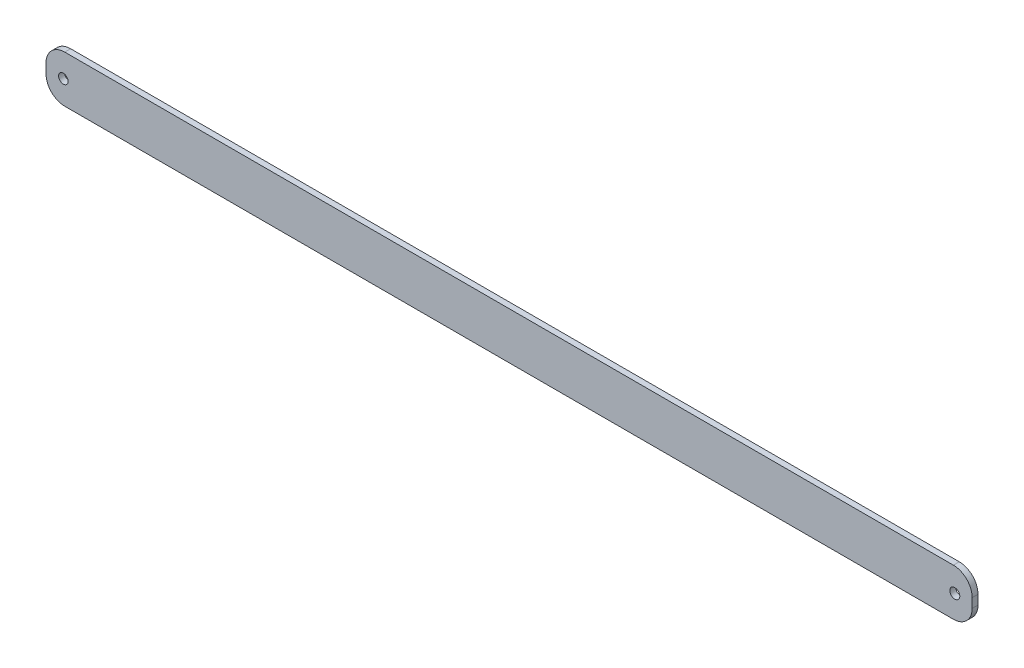
SolidWorks part; units mm, degrees
material "6061 Alloy"
ref_plane "Front Plane" through (0, 0, 0) normal (0, 0, 1) x (1, 0, 0)
ref_plane "Top Plane" through (0, 0, 0) normal (0, 1, 0) x (1, 0, 0)
ref_plane "Right Plane" through (0, 0, 0) normal (1, 0, 0) x (0, 0, -1)
sketch "Sketch1" plane through (0, 0, 0) normal (0, 0, 1) x (1, 0, 0)
  line L0 (-501.65, 0) -> (0, 0)
  line L1 (-501.65, 0) -> (-501.65, -25.4)
  line L2 (-501.65, -25.4) -> (0, -25.4)
  line L4 (0, -25.4) -> (0, 0)
  dimension "D1" = 501.65
  dimension "D2" = 25.4
  dimension "D3" = 25.4
  dimension "D4" = 501.65
extrude "Boss-Extrude1" add sketch "Sketch1" along normal blind 3.175
fillet "Fillet1" radius 10.16 1 edges at (0, 0, 1.5875)
fillet "Fillet2" radius 10.16 1 edges at (0, -25.4, 1.5875)
fillet "Fillet3" radius 10.16 1 edges at (-501.65, -25.4, 1.5875)
fillet "Fillet4" radius 10.16 1 edges at (-501.65, 0, 1.5875)
sketch "Sketch2" plane through (0, 0, 3.175) normal (0, 0, 1) x (1, 0, 0)
  line L0 (-501.65, -10.16) -> (-501.65, -15.24) construction
  circle A0 centre (-492.252, -12.8433) radius 2.5758
  dimension "D1" = 9.398
extrude "Cut-Extrude1" cut sketch "Sketch2" against normal through all
sketch "Sketch3" plane through (0, 0, 0) normal (0, 0, -1) x (-1, 0, 0)
  line L0 (0, -15.24) -> (0, -10.16) construction
  circle A0 centre (9.398, -12.8609) radius 2.7159
  dimension "D1" = 9.398
extrude "Cut-Extrude2" cut sketch "Sketch3" against normal through all
